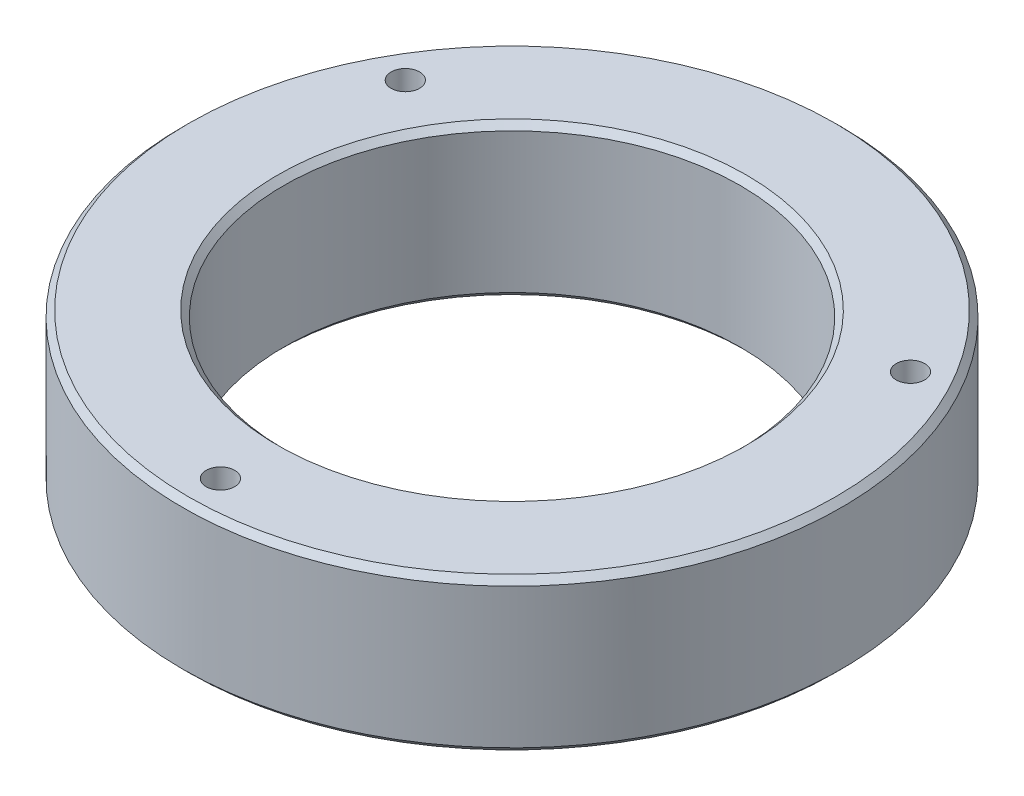
SolidWorks part; units mm, degrees
ref_plane "Front Plane" through (0, 0, 0) normal (1, 0, 0) x (0, 1, 0)
ref_plane "Top Plane" through (0, 0, 0) normal (0, 0, 1) x (0, 1, 0)
ref_plane "Right Plane" through (0, 0, 0) normal (0, 1, 0) x (-1, 0, 0)
sketch "Sketch1" plane through (0, 0, 0) normal (0, 0, 1) x (0, 1, 0)
  line L0 (-19.05, 82.5246) -> (19.05, 82.5246)
  line L1 (19.05, 82.5246) -> (19.05, 57.15)
  line L2 (19.05, 57.15) -> (-19.05, 57.15)
  line L3 (-19.05, 57.15) -> (-19.05, 82.5246)
  line L4 (-44.45, 0) -> (44.45, 0) construction
revolve "Revolve1" add sketch "Sketch1" angle 360 about L4
hole_wizard "CBORE for 1/4 Socket Head Cap Screw1" positions "Sketch3" profile "Sketch2" counterbore size "1/4" standard "ANSI Inch"
sketch "Sketch3" plane through (0, -19.05, 0) normal (0, -1, 0) x (-1, 0, 0)
  point P0 (0, -73.025)
  point P1 (-63.246, 36.5252)
  point P3 (63.246, 36.5252)
sketch "Sketch2" plane through (0, -19.05, 73.025) normal (1, 0, 0) x (0, 0, -1)
  line L0 (0, 0) -> (0, 40.2443)
  line L1 (0, 40.2443) -> (3.5687, 38.1)
  line L2 (3.5687, 38.1) -> (3.5687, 9.652)
  line L3 (3.5687, 9.652) -> (5.5626, 9.652)
  line L4 (5.5626, 9.652) -> (5.5626, 0)
  line L5 (5.5626, 0) -> (0, 0)
  line L10 (0, 40.2443) -> (-3.5687, 38.1) construction
  line L11 (0, -6.35) -> (0, 107.95) construction
  dimension "Hole Dia." = 7.1374
  dimension "Hole Depth" = 38.1
  dimension "C'Bore Dia." = 11.1252
  dimension "C'Bore Depth" = 9.652
  dimension "Drill Angle" = 118
sketch "Sketch4" plane through (0, 0, 0) normal (0, 1, 0) x (-1, 0, 0)
  circle A0 centre (-69.85, 0) radius 3.9687
  circle A1 centre (69.85, 0) radius 3.9687
extrude "Cut-Extrude2" cut sketch "Sketch4" along normal blind 25.4 from offset 19.05
chamfer "Chamfer1" distance 1.524 angle 45 4 edges at (0, 19.05, -57.15) (0, -19.05, -57.15) (0, 19.05, -82.5246) (0, -19.05, -82.5246)
